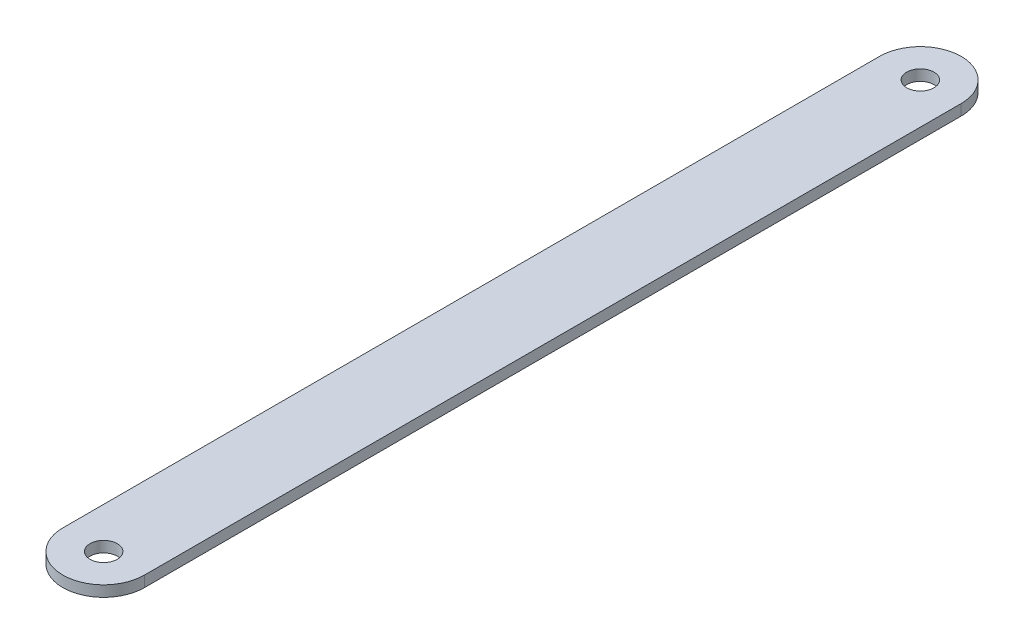
SolidWorks part; units mm, degrees
ref_plane "Front Plane" through (0, 0, 0) normal (0, 0, 1) x (1, 0, 0)
ref_plane "Top Plane" through (0, 0, 0) normal (0, 1, 0) x (1, 0, 0)
ref_plane "Right Plane" through (0, 0, 0) normal (1, 0, 0) x (0, 0, -1)
sketch "Sketch1" plane through (0, 0, 0) normal (0, 1, 0) x (1, 0, 0)
  line L2 (-15.6548, 108.5119) -> (-15.6548, -41.4881)
  line L4 (-0.6548, 108.5119) -> (-0.6548, -41.4881)
  arc A0 (-15.6548, 108.5119) -> (-0.6548, 108.5119) centre (-8.1548, 108.5119) cw
  arc A1 (-15.6548, -41.4881) -> (-0.6548, -41.4881) centre (-8.1548, -41.4881) ccw
  dimension "D1" = 15
extrude "Boss-Extrude1" add sketch "Sketch1" along normal mid plane 2
sketch "Sketch3" plane through (0, 1, 0) normal (0, 1, 0) x (1, 0, 0)
  circle A0 centre (-8.1548, 108.5119) radius 2.5
  circle A1 centre (-8.1548, -41.4881) radius 2.5
  arc A2 (-0.6548, 108.5119) -> (-15.6548, 108.5119) centre (-8.1548, 108.5119) ccw construction
  arc A3 (-15.6548, -41.4881) -> (-0.6548, -41.4881) centre (-8.1548, -41.4881) ccw construction
  dimension "D1" = 5
  dimension "D2" = 5
extrude "Cut-Extrude2" cut sketch "Sketch3" against normal blind 2
